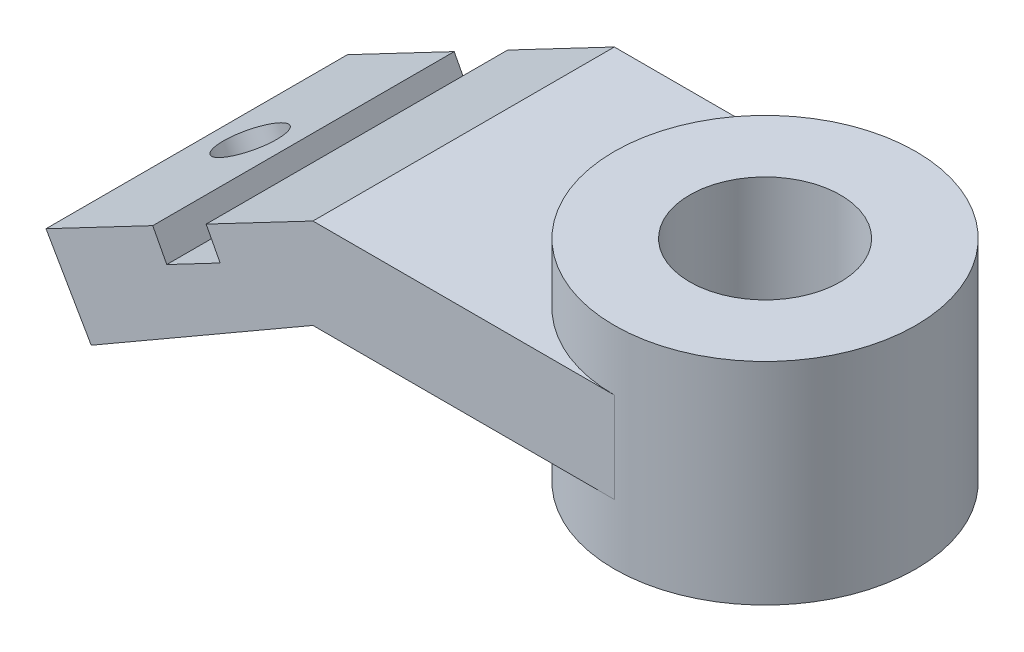
SolidWorks part; units mm, degrees
material "2018 Alloy"
ref_plane "Front Plane" through (0, 0, 0) normal (0, 0, 1) x (1, 0, 0)
ref_plane "Top Plane" through (0, 0, 0) normal (0, 1, 0) x (1, 0, 0)
ref_plane "Right Plane" through (0, 0, 0) normal (1, 0, 0) x (0, 0, -1)
sketch "Sketch1" plane through (0, 0, 0) normal (0, 1, 0) x (1, 0, 0)
  circle A0 centre (0, 0) radius 25
  circle A1 centre (0, 0) radius 12.5
  dimension "D1" = 50
  dimension "D2" = 25
extrude "Boss-Extrude1" add sketch "Sketch1" along normal mid plane 35
sketch "Sketch2" plane through (0, 0, 0) normal (0, 0, 1) x (1, 0, 0)
  line L0 (-15, 7.5) -> (-50, 7.5)
  line L1 (0, -7.5) -> (0, 7.5)
  line L2 (-50, 7.5) -> (-50, -7.5)
  line L3 (-50, -7.5) -> (-15, -7.5)
  line L5 (25, 17.5) -> (-25, 17.5) construction
  line L6 (-25, -17.5) -> (25, -17.5) construction
  line L8 (0, 7.5) -> (-15, 7.5)
  line L9 (-15, -7.5) -> (0, -7.5)
  line L10 (-25, 17.5) -> (-25, -17.5) construction
  dimension "D1" = 15
  dimension "D2" = 10
  dimension "D3" = 25
  dimension "D4" = 10
  dimension "D5" = 25
extrude "Boss-Extrude2" add sketch "Sketch2" along normal mid plane 50
sketch "Sketch3" plane through (0, 17.5, 0) normal (0, 1, 0) x (1, 0, 0)
  circle A0 centre (0, 0) radius 12.5 construction
  circle A1 centre (0, 0) radius 12.5
extrude "Cut-Extrude1" cut sketch "Sketch3" against normal blind 50
sketch "Sketch4" plane through (0, 0, 0) normal (0, 0, 1) x (1, 0, 0)
  line L2 (-50, 7.5) -> (-94.2711, -15.7394)
  line L7 (-50, -7.5) -> (-86.7711, -28.7298)
  line L8 (-50, -7.5) -> (0, -7.5) construction
  line L9 (-50, 7.5) -> (-50, -7.5) construction
  line L10 (-50, 7.5) -> (-50, -7.5)
  line L11 (-94.2711, -15.7394) -> (-86.7711, -28.7298)
  dimension "D1" = 15
  dimension "D2" = 50
  dimension "D3" = 150
  dimension "D4" = 15
extrude "Boss-Extrude3" add sketch "Sketch4" along normal mid plane 50
sketch "Sketch5" plane through (-13.8879, 26.4565, 0) normal (-0.4648, 0.8854, 0) x (0.8854, 0.4648, 0)
  line L0 (-65.7852, 25) -> (-65.7852, -25) construction
  line L1 (-40.7852, 25) -> (-90.7852, 25) construction
  line L2 (-40.7852, -25) -> (-90.7852, -25) construction
  line L4 (-60.7852, 37.9891) -> (-70.7852, 37.9891)
  line L5 (-60.7852, 37.9891) -> (-60.7852, -37.9891)
  line L6 (-60.7852, -37.9891) -> (-70.7852, -37.9891)
  line L7 (-70.7852, 37.9891) -> (-70.7852, -37.9891)
  line L8 (-60.7852, 37.9891) -> (-70.7852, -37.9891) construction
  line L9 (-60.7852, -37.9891) -> (-70.7852, 37.9891) construction
  point P6 (-65.7852, 0)
  dimension "D1" = 10
extrude "Cut-Extrude2" cut sketch "Sketch5" against normal blind 5
sketch "Sketch6" plane through (-13.8879, 26.4565, 0) normal (-0.4648, 0.8854, 0) x (0.8854, 0.4648, 0)
  line L0 (-70.7852, 0) -> (-90.7852, 0) construction
  line L1 (-70.7852, -25) -> (-70.7852, 25) construction
  line L2 (-90.7852, -25) -> (-90.7852, 25) construction
  circle A0 centre (-80.7852, 0) radius 5
  dimension "D1" = 10
extrude "Cut-Extrude3" cut sketch "Sketch6" against normal through all
